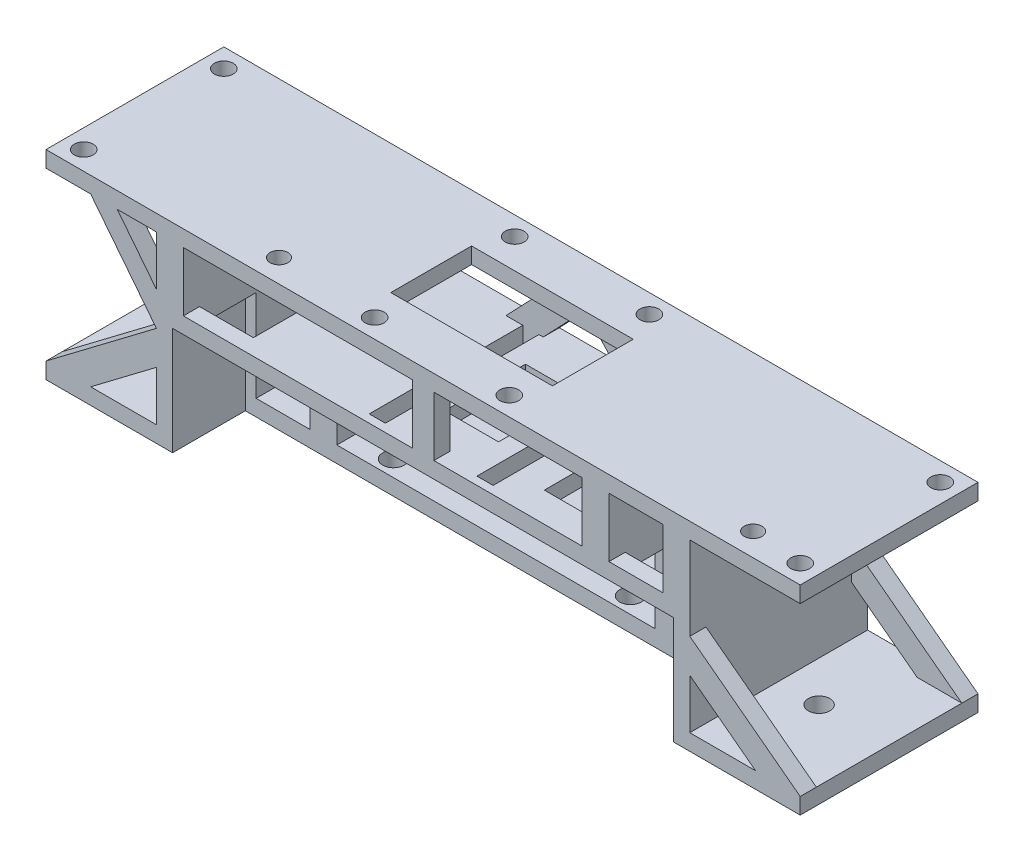
SolidWorks part; units mm, degrees
ref_plane "前视基准面" through (0, 0, 0) normal (0, 0, 1) x (1, 0, 0)
ref_plane "上视基准面" through (0, 0, 0) normal (0, 1, 0) x (1, 0, 0)
ref_plane "右视基准面" through (0, 0, 0) normal (1, 0, 0) x (0, 0, -1)
sketch "草图1" plane through (0, 0, 0) normal (0, 1, 0) x (1, 0, 0)
  line L1 (-70, -16.5) -> (70, -16.5)
  line L2 (-70, -16.5) -> (-70, 16.5)
  line L3 (-70, 16.5) -> (70, 16.5)
  line L4 (70, -16.5) -> (70, 16.5)
  line L5 (-70, -16.5) -> (70, 16.5) construction
  line L6 (-70, 16.5) -> (70, -16.5) construction
  point P0 (0, 0)
  dimension "D1" = 140
  dimension "D2" = 33
extrude "凸台-拉伸1" add sketch "草图1" along normal blind 3
sketch "草图2" plane through (0, 3, 0) normal (0, 1, 0) x (1, 0, 0)
  line L0 (70, 16.5) -> (-70, 16.5) construction
  line L1 (-70, -16.5) -> (-9, -16.5)
  line L2 (-70, -16.5) -> (-70, 16.5)
  line L3 (-70, 16.5) -> (-9, 16.5)
  line L4 (-9, -16.5) -> (-9, 16.5)
  line L6 (70, -16.5) -> (9, -16.5)
  line L7 (70, -16.5) -> (70, 16.5)
  line L8 (70, 16.5) -> (9, 16.5)
  line L9 (9, -16.5) -> (9, 16.5)
  point P12 (-66.5, 13)
  point P13 (-12.5, 13)
  point P14 (-66.5, -13)
  point P15 (-12.5, -13)
  dimension "D1" = 61
  dimension "D2" = 61
  dimension "D3" = 3.5
  dimension "D4" = 3.5
  dimension "D5" = 3.5
  dimension "D6" = 3.5
  dimension "D7" = 3.5
  dimension "D8" = 3.5
  dimension "D9" = 3.5
  dimension "D10" = 3.5
sketch "草图3" plane through (0, 3, 0) normal (0, 1, 0) x (1, 0, 0)
  point P0 (-66.5, 13)
  point P3 (-12.5, 13)
  point P6 (-12.5, -13)
  point P9 (-66.5, -13)
hole_wizard "孔1" positions "草图3" profile "草图4" legacy end condition through all
sketch "草图4" plane through (-66.5, 3, -13) normal (1, 0, 0) x (0, 0, 1)
  line L0 (0, 0) -> (0, 3)
  line L1 (0, 3) -> (1.75, 3)
  line L2 (1.75, 3) -> (1.75, 0)
  line L3 (1.75, 0) -> (0, 0)
  line L4 (0, 110) -> (0, -10) construction
  dimension "直径" = 3.5
  dimension "深度" = 3
ref_plane "基准面4" through (0, 0, 0) normal (-1, 0, 0) x (0, 0, 1)
mirror "镜向1" about plane through (0, 0, 0) normal (-1, 0, 0) of "孔1"
sketch "草图5" plane through (0, 0, 0) normal (0, -1, 0) x (1, 0, 0)
  line L0 (-39.5, 16.5) -> (-39.5, -16.5)
  line L1 (-70, 16.5) -> (-9, 16.5) construction
  line L2 (-70, -16.5) -> (-9, -16.5) construction
  line L3 (39.5, 16.5) -> (39.5, -16.5)
  line L4 (70, 16.5) -> (9, 16.5) construction
  line L5 (70, -16.5) -> (9, -16.5) construction
  line L7 (-49.5, -16.5) -> (-29.5, -16.5)
  line L8 (-49.5, -16.5) -> (-49.5, 16.5)
  line L9 (-49.5, 16.5) -> (-29.5, 16.5)
  line L10 (-29.5, -16.5) -> (-29.5, 16.5)
  line L11 (-49.5, -16.5) -> (-29.5, 16.5) construction
  line L12 (-49.5, 16.5) -> (-29.5, -16.5) construction
  line L13 (29.5, -16.5) -> (49.5, -16.5)
  line L14 (29.5, -16.5) -> (29.5, 16.5)
  line L15 (29.5, 16.5) -> (49.5, 16.5)
  line L16 (49.5, -16.5) -> (49.5, 16.5)
  line L17 (29.5, -16.5) -> (49.5, 16.5) construction
  line L18 (29.5, 16.5) -> (49.5, -16.5) construction
  point P12 (-39.5, 0)
  point P17 (39.5, 0)
  line M7 (70, 16.5) -> (-70, 16.5)
  line M9 (-70, -16.5) -> (70, -16.5)
  dimension "D1" = 20
  dimension "D2" = 20
extrude "凸台-拉伸2" add sketch "草图5" along normal blind 31 contours L8 L0 M9 M7 | L10 L0 M9 M7 | L14 L3 M9 M7 | L16 L3 M9 M7
sketch "草图6" plane through (0, -31, 0) normal (0, -1, 0) x (1, 0, 0)
  line L1 (-70, 16.5) -> (70, 16.5)
  line L2 (-70, 16.5) -> (-70, -16.5)
  line L3 (-70, -16.5) -> (70, -16.5)
  line L4 (70, 16.5) -> (70, -16.5)
extrude "凸台-拉伸3" add sketch "草图6" along normal blind 3
sketch "草图7" plane through (0, -34, 0) normal (0, -1, 0) x (1, 0, 0)
  line L0 (-70, 0) -> (-9, 0)
  line L1 (-70, 16.5) -> (-9, 16.5)
  line L2 (-70, 16.5) -> (-70, -16.5)
  line L3 (-70, -16.5) -> (-9, -16.5)
  line L4 (-9, 16.5) -> (-9, -16.5)
  line L5 (9, -16.5) -> (70, -16.5)
  line L6 (9, -16.5) -> (9, 16.5)
  line L7 (9, 16.5) -> (70, 16.5)
  line L8 (70, -16.5) -> (70, 16.5)
  point P14 (-39.5, 0)
  point P15 (-57, 0)
  point P16 (-22, 0)
  dimension "D1" = 17.5
  dimension "D2" = 17.5
sketch "草图8" plane through (0, -34, 0) normal (0, -1, 0) x (-1, 0, 0)
  point P0 (57, 0)
  point P3 (22, 0)
hole_wizard "孔2" positions "草图8" profile "草图9" legacy
sketch "草图9" plane through (-57, -34, 0) normal (1, 0, 0) x (0, 0, -1)
  line L0 (0, 0) -> (0, 3)
  line L1 (0, 3) -> (2, 3)
  line L2 (2, 3) -> (2, 0)
  line L3 (2, 0) -> (0, 0)
  line L4 (0, 110) -> (0, -10) construction
  dimension "直径" = 4
  dimension "深度" = 3
mirror "镜向2" about plane through (0, 0, 0) normal (-1, 0, 0) of "孔2"
sketch "草图10" plane through (0, 0, 16.5) normal (0, 0, 1) x (1, 0, 0)
  line L0 (-70, -31) -> (-49.5, -15.5)
  line L1 (-49.5, -31) -> (-49.5, 0) construction
  line L2 (-49.5, -15.5) -> (-49.5, -31)
  line L3 (-49.5, -31) -> (-70, -31) construction
  line L4 (-49.5, -31) -> (-70, -31)
  line L5 (-49.5, -15.5) -> (-70, 0)
  line L6 (-70, 0) -> (-49.5, 0)
  line L7 (-49.5, 0) -> (-49.5, -15.5)
  line L8 (-61.7096, 0) -> (-49.5, -9.2317)
  line L9 (-61.7096, -31) -> (-49.5, -21.7683)
  line L10 (-61.7096, 0) -> (-49.5, -15.5)
  line L11 (-49.5, -9.2317) -> (-56.7719, 0)
  point P5 (-49.5, -15.5)
  dimension "D1" = 5
  dimension "D2" = 5
extrude "凸台-拉伸7" add sketch "草图10" against normal blind 3 contours L8 L10 L7 | L8 L11 L6 | L4 L9 L2 L0
ref_plane "基准面5" through (0, 0, 0) normal (0, 0, 1) x (1, 0, 0)
mirror "镜向3" about plane through (0, 0, 0) normal (0, 0, 1) of "凸台-拉伸7"
mirror "镜向4" about plane through (0, 0, 0) normal (-1, 0, 0) of "凸台-拉伸7", "镜向3"
sketch "草图11" plane through (0, 0, 16.5) normal (0, 0, 1) x (1, 0, 0)
  line L0 (-29.5, -31) -> (0, 0)
  line L1 (0, 0) -> (29.5, -31)
  line L2 (-29.5, -26.6482) -> (-4.1413, 0)
  line L3 (-29.5, -31) -> (-29.5, 0) construction
  line L4 (-29.5, 0) -> (29.5, 0) construction
  line L5 (4.1413, 0) -> (29.5, -26.6482)
  line L6 (29.5, -31) -> (29.5, 0) construction
  line L7 (-26.7392, -31) -> (1.3804, -1.4506)
  line L8 (29.5, -31) -> (-29.5, -31) construction
  line L9 (-1.3804, -1.4506) -> (26.7392, -31)
  line L10 (-29.5, -26.6482) -> (-29.5, -31)
  line L11 (-29.5, -31) -> (-26.7392, -31)
  line L12 (-4.1413, 0) -> (4.1413, 0)
  line L13 (29.5, -31) -> (29.5, -26.6482)
  line L14 (26.7392, -31) -> (29.5, -31)
  line M29 (29.5, -31) -> (-29.5, -31)
  line M30 (-29.5, -31) -> (-29.5, 0)
  line M31 (-29.5, 0) -> (29.5, 0)
  line M32 (29.5, 0) -> (29.5, -31)
  dimension "D1" = 3
  dimension "D2" = 3
  dimension "D3" = 2
  dimension "D4" = 2
extrude "凸台-拉伸8" add sketch "草图11" against normal blind 3 contours L9 L0 L7 M29 | L2 L0 M30 M31 | L0 L9 L7 L1 | L7 L9 L1 M29 | L5 L1 M31 M32
mirror "镜向5" about plane through (0, 0, 0) normal (0, 0, 1) of "凸台-拉伸8"
sketch "草图12" plane through (0, 0, 16.5) normal (0, 0, 1) x (1, 0, 0)
  line L0 (-56.7719, 0) -> (-49.5, 0) construction
  line L1 (-44.5, 0) -> (-34.5, 0)
  line L2 (-44.5, 0) -> (-44.5, -31)
  line L3 (-44.5, -31) -> (-34.5, -31)
  line L4 (-34.5, 0) -> (-34.5, -31)
  line L5 (-49.5, -31) -> (-61.7096, -31) construction
  line L6 (-29.5, -26.6482) -> (-29.5, 0) construction
  line L7 (-49.5, -31) -> (-49.5, -21.7683) construction
  dimension "D1" = 5
  dimension "D2" = 5
extrude "切除-拉伸1" cut sketch "草图12" against normal through all
mirror "镜向6" about plane through (0, 0, 0) normal (-1, 0, 0) of "切除-拉伸1"
sketch "草图14" plane through (0, -31, 0) normal (0, 1, 0) x (1, 0, 0)
  line L0 (0, -16.5) -> (0, -9.5)
  line L1 (-70, -16.5) -> (70, -16.5) construction
  line L2 (0, 1.65) -> (0, -1.65) construction
  line L4 (-9, -11.15) -> (9, -11.15)
  line L5 (-9, -11.15) -> (-9, -7.85)
  line L6 (-9, -7.85) -> (9, -7.85)
  line L7 (9, -11.15) -> (9, -7.85)
  line L8 (-9, -11.15) -> (9, -7.85) construction
  line L9 (-9, -7.85) -> (9, -11.15) construction
  dimension "D1" = 7
  dimension "D2" = 3.3
  dimension "D3" = 18
extrude "切除-拉伸3" cut sketch "草图14" against normal blind 3
sketch "草图17" plane through (0, 3, 0) normal (0, 1, 0) x (1, 0, 0)
  line L1 (-15, -7.5) -> (15, -7.5)
  line L2 (-15, -7.5) -> (-15, 7.5)
  line L3 (-15, 7.5) -> (15, 7.5)
  line L4 (15, -7.5) -> (15, 7.5)
  line L5 (-15, -7.5) -> (15, 7.5) construction
  line L6 (-15, 7.5) -> (15, -7.5) construction
  point P0 (0, 0)
  dimension "D1" = 15
  dimension "D2" = 30
extrude "切除-拉伸5" cut sketch "草图17" against normal blind 5
sketch "草图18" plane through (0, 0, 16.5) normal (0, 0, 1) x (1, 0, 0)
  line L1 (-26.7392, -31) -> (26.7392, -31)
  line L2 (-26.7392, -31) -> (-26.7392, -28)
  line L3 (-26.7392, -28) -> (26.7392, -28)
  line L4 (26.7392, -31) -> (26.7392, -28)
  dimension "D1" = 3
sketch "草图22" plane through (0, 0, 16.5) normal (0, 0, 1) x (1, 0, 0)
  line L1 (49.5, 0) -> (64.5, 0)
  line L2 (49.5, 0) -> (49.5, -15.5)
  line L3 (49.5, -15.5) -> (64.5, -15.5)
  line L4 (64.5, 0) -> (64.5, -15.5)
  dimension "D1" = 15
extrude "切除-拉伸6" cut sketch "草图22" against normal blind 3
sketch "草图23" plane through (0, 0, 16.5) normal (0, 0, 1) x (1, 0, 0)
  line L0 (0, 3) -> (0, -34)
  line L1 (-70, 3) -> (70, 3) construction
  line L2 (70, -34) -> (-70, -34) construction
  line L3 (9, -34) -> (70, -34) construction
  line L4 (-46.5, -34) -> (46.5, -34)
  line L5 (-46.5, -34) -> (-46.5, -14)
  line L6 (-46.5, -14) -> (46.5, -14)
  line L7 (46.5, -34) -> (46.5, -14)
  line L8 (-46.5, -34) -> (46.5, -14) construction
  line L9 (-46.5, -14) -> (46.5, -34) construction
  point P6 (0, -24)
  dimension "D1" = 93
  dimension "D2" = 20
extrude "切除-拉伸7" cut sketch "草图23" against normal blind 13.5 contours L6 L7 L4 L5
sketch "草图24" plane through (0, 0, 16.5) normal (0, 0, 1) x (1, 0, 0)
  line L1 (-29.5, 0) -> (29.5, 0)
  line L2 (-29.5, 0) -> (-29.5, -14)
  line L3 (-29.5, -14) -> (29.5, -14)
  line L4 (29.5, 0) -> (29.5, -14)
extrude "切除-拉伸8" cut sketch "草图24" against normal blind 3
sketch "草图26" plane through (0, 0, 16.5) normal (0, 0, 1) x (1, 0, 0)
  line L0 (29.5, -14) -> (29.5, 0) construction
  line L1 (-29.5, -14) -> (29.5, -14)
  line L2 (-29.5, -14) -> (-29.5, -11)
  line L3 (-29.5, -11) -> (29.5, -11)
  line L4 (29.5, -14) -> (29.5, -11)
  dimension "D1" = 3
extrude "凸台-拉伸9" add sketch "草图26" against normal up to vertex (33 mm away) up to point (-70, -34, -16.5)
sketch "草图27" plane through (0, -11, 0) normal (0, 1, 0) x (1, 0, 0)
  line L1 (-10, -15) -> (10, -15)
  line L2 (-10, -15) -> (-10, 15)
  line L3 (-10, 15) -> (10, 15)
  line L4 (10, -15) -> (10, 15)
  line L5 (-10, -15) -> (10, 15) construction
  line L6 (-10, 15) -> (10, -15) construction
  line L7 (-11.5, -15) -> (-8.5, -15)
  line L8 (-11.5, -15) -> (-11.5, 15)
  line L9 (-11.5, 15) -> (-8.5, 15)
  line L10 (-8.5, -15) -> (-8.5, 15)
  line L11 (-11.5, -15) -> (-8.5, 15) construction
  line L12 (-11.5, 15) -> (-8.5, -15) construction
  line L13 (11.5, -15) -> (8.5, -15)
  line L14 (11.5, -15) -> (11.5, 15)
  line L15 (11.5, 15) -> (8.5, 15)
  line L16 (8.5, -15) -> (8.5, 15)
  line L17 (11.5, -15) -> (8.5, 15) construction
  line L18 (11.5, 15) -> (8.5, -15) construction
  point P0 (0, 0)
  point P6 (-10, 0)
  point P11 (10, 0)
  line M6 (-7.7069, 13.5) -> (-14.609, 13.5)
  line M14 (14.609, 13.5) -> (7.7069, 13.5)
  dimension "D1" = 20
  dimension "D2" = 30
  dimension "D3" = 3
  dimension "D4" = 3
extrude "切除-拉伸9" cut sketch "草图27" against normal blind 3 contours L8 L7 L2 M6 | L1 L10 L2 M6 | L16 L1 L4 M14 | L13 L14 L4 M14
sketch "草图28" plane through (0, 0, 16.5) normal (0, 0, 1) x (1, 0, 0)
  line L0 (-34.5, -14) -> (-34.5, 0) construction
  line L1 (-44.5, -14) -> (-34.5, -14)
  line L2 (-44.5, -14) -> (-44.5, -11)
  line L3 (-44.5, -11) -> (-34.5, -11)
  line L4 (-34.5, -14) -> (-34.5, -11)
  line L5 (44.5, 0) -> (44.5, -14) construction
  line L6 (34.5, -14) -> (44.5, -14)
  line L7 (34.5, -14) -> (34.5, -11)
  line L8 (34.5, -11) -> (44.5, -11)
  line L9 (44.5, -14) -> (44.5, -11)
  dimension "D1" = 3
  dimension "D2" = 3
extrude "凸台-拉伸10" add sketch "草图28" against normal blind 3
sketch "草图29" plane through (0, -11, 0) normal (0, 1, 0) x (1, 0, 0)
  line L1 (-5, -7.5) -> (5, -7.5)
  line L2 (-5, -7.5) -> (-5, 7.5)
  line L3 (-5, 7.5) -> (5, 7.5)
  line L4 (5, -7.5) -> (5, 7.5)
  line L5 (-5, -7.5) -> (5, 7.5) construction
  line L6 (-5, 7.5) -> (5, -7.5) construction
  point P0 (0, 0)
  dimension "D1" = 15
  dimension "D2" = 10
extrude "切除-拉伸10" cut sketch "草图29" against normal blind 3
sketch "草图30" plane through (0, 0, 16.5) normal (0, 0, 1) x (1, 0, 0)
  line L0 (0, 0) -> (0, -11)
  line L1 (-29.5, 0) -> (29.5, 0) construction
  line L2 (29.5, -11) -> (-29.5, -11) construction
  line L4 (-2, 0) -> (2, 0)
  line L5 (-2, 0) -> (-2, -11)
  line L6 (-2, -11) -> (2, -11)
  line L7 (2, 0) -> (2, -11)
  line L8 (-2, 0) -> (2, -11) construction
  line L9 (-2, -11) -> (2, 0) construction
  point P6 (0, -5.5)
  dimension "D1" = 4
extrude "凸台-拉伸11" add sketch "草图30" against normal blind 3 contours L5 L6 L7 L4
sketch "草图31" plane through (0, -11, 0) normal (0, 1, 0) x (1, 0, 0)
  line L0 (15, 0) -> (11.5, 0)
  line L1 (15, -7.5) -> (15, 7.5) construction
  line L2 (-20.35, 0) -> (20.35, 0) construction
  line L3 (11.5, -15) -> (11.5, 13.5) construction
  line L4 (11.5, 0) -> (29.5, 0)
  line L5 (29.5, 16.5) -> (29.5, -16.5) construction
  line L7 (17, 11) -> (24, 11)
  line L8 (17, 11) -> (17, -11)
  line L9 (17, -11) -> (24, -11)
  line L10 (24, 11) -> (24, -11)
  line L11 (17, 11) -> (24, -11) construction
  line L12 (17, -11) -> (24, 11) construction
  point P8 (20.5, 0)
  dimension "D1" = 22
  dimension "D2" = 7
extrude "切除-拉伸11" cut sketch "草图31" against normal up to next contours L10 L4 L8 L9 | L10 L7 L8 L4
sketch "草图32" plane through (0, 3, 0) normal (0, 1, 0) x (1, 0, 0)
  line L0 (70, -16.5) -> (9, -16.5) construction
  line L1 (70, -16.5) -> (70, 16.5) construction
  line L2 (57, -12.25) -> (-31, -12.25)
  point P0 (57, -12.25)
  dimension "D1" = 4.25
  dimension "D2" = 13
  dimension "D3" = 88
sketch "草图33" plane through (0, 3, 0) normal (0, 1, 0) x (1, 0, 0)
  point P0 (57, -12.25)
  point P3 (-31, -12.25)
sketch "草图35" plane through (0, 0, 16.5) normal (0, 0, 1) x (1, 0, 0)
  line L1 (-34.5, 0) -> (-29.5, 0)
  line L2 (-34.5, 0) -> (-34.5, -11)
  line L3 (-34.5, -11) -> (-29.5, -11)
  line L4 (-29.5, 0) -> (-29.5, -11)
extrude "切除-拉伸12" cut sketch "草图35" against normal blind 13.5
hole_wizard "孔3" positions "草图33" profile "草图34" legacy
sketch "草图34" plane through (57, 3, 12.25) normal (1, 0, 0) x (0, 0, 1)
  line L0 (0, 0) -> (0, 3)
  line L1 (0, 3) -> (1.65, 3)
  line L2 (1.65, 3) -> (1.65, 0)
  line L3 (1.65, 0) -> (0, 0)
  line L4 (0, 110) -> (0, -10) construction
  dimension "直径" = 3.3
  dimension "深度" = 3
